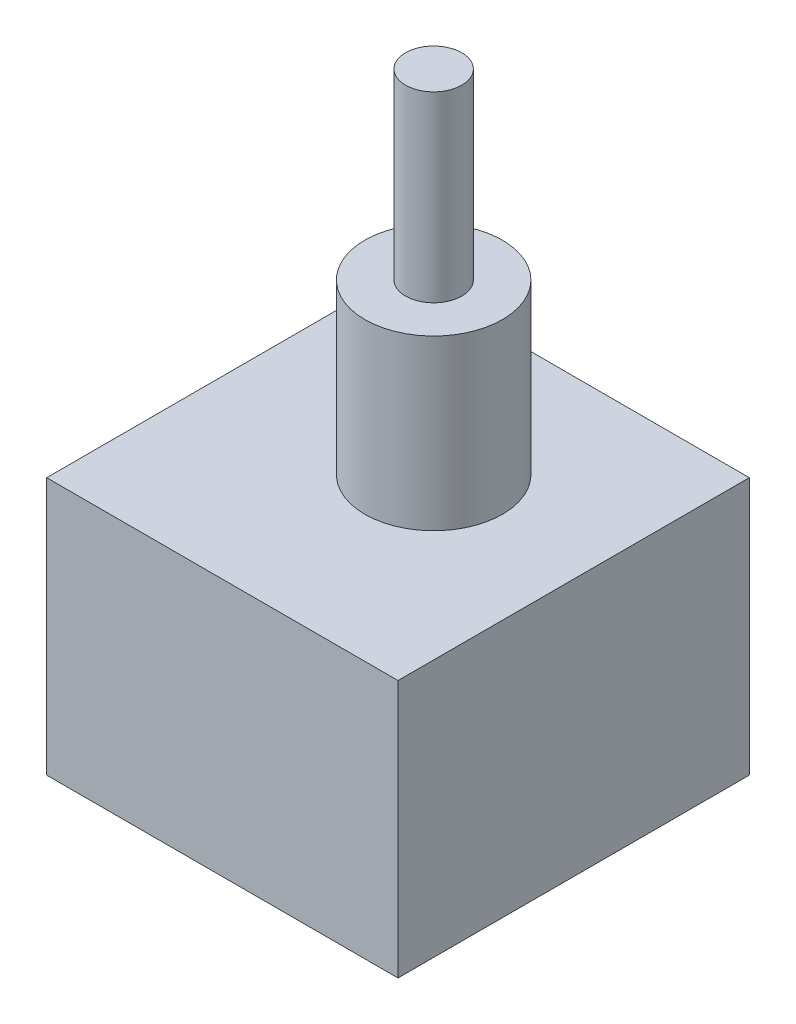
SolidWorks part; units mm, degrees
ref_plane "Спереди" through (0, 0, 0) normal (0, 0, 1) x (1, 0, 0)
ref_plane "Сверху" through (0, 0, 0) normal (0, 1, 0) x (1, 0, 0)
ref_plane "Справа" through (0, 0, 0) normal (1, 0, 0) x (0, 0, -1)
other "Configuration Table"
sketch "Эскиз1" plane through (0, 0, 0) normal (0, 1, 0) x (1, 0, 0)
  line L1 (-16.2944, 13.2487) -> (13.7056, 13.2487)
  line L2 (-16.2944, 13.2487) -> (-16.2944, -16.7513)
  line L3 (-16.2944, -16.7513) -> (13.7056, -16.7513)
  line L4 (13.7056, 13.2487) -> (13.7056, -16.7513)
  dimension "D1" = 30
  dimension "D2" = 30
extrude "высота " add sketch "Эскиз1" along normal blind 22
sketch "Эскиз2" plane through (0, 22, 0) normal (0, 1, 0) x (1, 0, 0)
  circle A0 centre (0, 0) radius 5.875
  dimension "D1" = 11.75
sketch "Эскиз3" plane through (0, 0, 0) normal (0, 0, 1) x (1, 0, 0)
  line L0 (0, 49.97) -> (0, -1.7648) construction
extrude "Бобышка-Вытянуть2" add sketch "Эскиз2" along normal blind 14.4 contours A0
sketch "Эскиз4" plane through (0, 36.4, 0) normal (0, 1, 0) x (1, 0, 0)
  circle A0 centre (0, 0) radius 2.4
  dimension "D1" = 4.8
extrude "Бобышка-Вытянуть3" add sketch "Эскиз4" along normal blind 15.6
sketch "Эскиз5" plane through (0, 0, 0) normal (0, -1, 0) x (1, 0, 0)
  line L0 (0, 0) -> (24.0796, 0) construction
  line L1 (0, 0) -> (0, 34.2465) construction
  circle A0 centre (7, 0) radius 2.5
  circle A1 centre (-7, 0) radius 2.5
  dimension "D1" = 5
  dimension "D2" = 7
extrude "Вырез-Вытянуть1" cut sketch "Эскиз5" against normal blind 15
